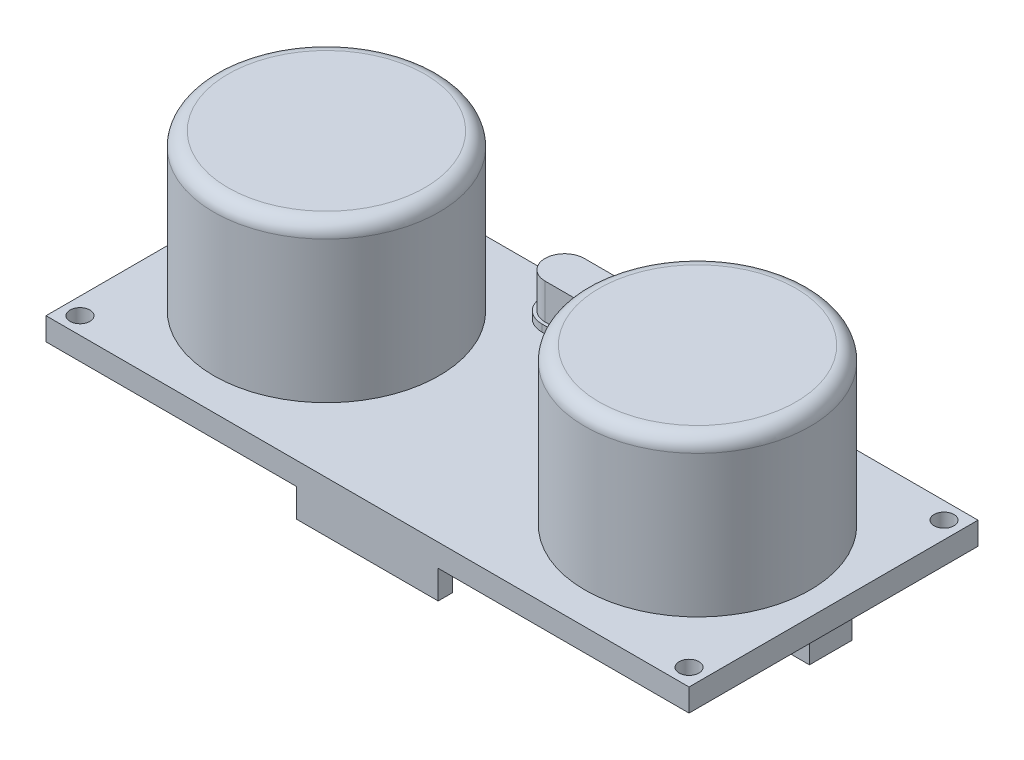
SolidWorks part; units mm, degrees
ref_plane "Alzado" through (0, 0, 0) normal (0, 0, 1) x (1, 0, 0)
ref_plane "Planta" through (0, 0, 0) normal (0, 1, 0) x (1, 0, 0)
ref_plane "Vista lateral" through (0, 0, 0) normal (1, 0, 0) x (0, 0, -1)
sketch "Croquis1" plane through (0, 0, 0) normal (0, 1, 0) x (1, 0, 0)
  line L1 (-22.7, 10.2) -> (22.7, 10.2)
  line L2 (-22.7, 10.2) -> (-22.7, -10.2)
  line L3 (-22.7, -10.2) -> (22.7, -10.2)
  line L4 (22.7, 10.2) -> (22.7, -10.2)
  line L5 (-22.7, 10.2) -> (22.7, -10.2) construction
  line L6 (-22.7, -10.2) -> (22.7, 10.2) construction
  point P0 (0, 0)
  dimension "D1" = 45.4
  dimension "D2" = 20.4
extrude "Saliente-Extruir1" add sketch "Croquis1" along normal blind 1.6
sketch "Croquis2" plane through (0, 1.6, 0) normal (0, 1, 0) x (1, 0, 0)
  line L5 (-21.5, 9) -> (21.5, -9) construction
  line L6 (-21.5, -9) -> (21.5, 9) construction
  circle A0 centre (-21.5, 9) radius 0.7
  circle A1 centre (21.5, 9) radius 0.7
  circle A2 centre (21.5, -9) radius 0.7
  circle A3 centre (-21.5, -9) radius 0.7
  point P0 (0, 0)
  dimension "D3" = 1.4
  dimension "D1" = 43
  dimension "D2" = 18
extrude "Cortar-Extruir1" cut sketch "Croquis2" against normal blind 1
sketch "Croquis3" plane through (0, 1.6, 0) normal (0, 1, 0) x (1, 0, 0)
  line L0 (0, 10.2) -> (0, -10.2) construction
  line L1 (22.7, 10.2) -> (-22.7, 10.2) construction
  line L2 (-22.7, -10.2) -> (22.7, -10.2) construction
  line L3 (-4.2022, 7.9196) -> (4.2022, 7.9196) construction
  line L4 (-4.2022, 9.5358) -> (4.2022, 9.5358)
  line L5 (-4.2022, 6.3033) -> (4.2022, 6.3033)
  line L6 (-4.2022, 7.9196) -> (4.2022, 7.9196) construction
  line L7 (-4.2022, 9.3049) -> (4.2022, 9.3049)
  line L8 (-4.2022, 6.5342) -> (4.2022, 6.5342)
  arc A0 (-4.2022, 9.5358) -> (-4.2022, 6.3033) centre (-4.2022, 7.9196) ccw
  arc A1 (4.2022, 6.3033) -> (4.2022, 9.5358) centre (4.2022, 7.9196) ccw
  arc A2 (-4.2022, 9.3049) -> (-4.2022, 6.5342) centre (-4.2022, 7.9196) ccw
  arc A3 (4.2022, 6.5342) -> (4.2022, 9.3049) centre (4.2022, 7.9196) ccw
  point P8 (0, 7.9196)
  point P15 (0, 7.9196)
extrude "Saliente-Extruir2" add sketch "Croquis3" along normal blind 0.5 contours L8 A3 L7 A2 | L5 A1 L4 A0
sketch "Croquis8" plane through (0, 1.6, 0) normal (0, 1, 0) x (1, 0, 0)
  line L0 (-4.2022, 9.3049) -> (4.2022, 9.3049) construction
  line L1 (-4.2022, 6.5342) -> (4.2022, 6.5342) construction
  line L2 (-4.2022, 9.3049) -> (4.2022, 9.3049)
  line L3 (-4.2022, 6.5342) -> (4.2022, 6.5342)
  arc A0 (4.2022, 6.5342) -> (4.2022, 9.3049) centre (4.2022, 7.9196) ccw construction
  arc A1 (-4.2022, 9.3049) -> (-4.2022, 6.5342) centre (-4.2022, 7.9196) ccw construction
  arc A2 (4.2022, 6.5342) -> (4.2022, 9.3049) centre (4.2022, 7.9196) ccw
  arc A3 (-4.2022, 9.3049) -> (-4.2022, 6.5342) centre (-4.2022, 7.9196) ccw
extrude "Saliente-Extruir3" add sketch "Croquis8" along normal blind 3
sketch "Croquis9" plane through (0, 1.6, 0) normal (0, 1, 0) x (1, 0, 0)
  line L0 (-21.05, 0) -> (21.05, 0) construction
  line L3 (-22.7, 10.2) -> (0, -10.2) construction
  line L4 (-22.7, -10.2) -> (22.7, -10.2) construction
  line L5 (0, -10.2) -> (22.7, 10.2) construction
  line L6 (-22.7, -10.2) -> (0, 10.2) construction
  line L7 (22.7, 10.2) -> (-22.7, 10.2) construction
  line L8 (0, 10.2) -> (22.7, -10.2) construction
  circle A0 centre (-13.1, 0) radius 7.95
  circle A1 centre (13.1, 0) radius 7.95
  point P2 (0, 0)
  dimension "D1" = 15.9
  dimension "D2" = 15.9
  dimension "D3" = 42.1
extrude "Saliente-Extruir4" add sketch "Croquis9" along normal blind 11
sketch "Croquis10" plane through (0, 0, 0) normal (0, -1, 0) x (1, 0, 0)
  line L0 (0, 10.2) -> (0, -10.2) construction
  line L1 (-22.7, 10.2) -> (22.7, 10.2) construction
  line L2 (22.7, -10.2) -> (-22.7, -10.2) construction
  line L3 (22.7, 0) -> (-22.7, 0) construction
  line L4 (22.7, 10.2) -> (22.7, -10.2) construction
  line L5 (-22.7, -10.2) -> (-22.7, 10.2) construction
  line L6 (-5.0127, 10.2) -> (4.9873, 10.2)
  line L7 (-5.0127, 10.2) -> (-5.0127, 9.2)
  line L8 (-5.0127, 9.2) -> (4.9873, 9.2)
  line L9 (4.9873, 9.2) -> (4.9873, 10.2)
  point P15 (-0.0127, 10.2)
  dimension "D1" = 10
  dimension "D2" = 1
extrude "Saliente-Extruir5" add sketch "Croquis10" along normal blind 2
fillet "Redondeo5" radius 1 2 edges at (13.1, 12.6, 7.95) (-13.1, 12.6, 7.95)
sketch "Croquis13" plane through (0, 0, 0) normal (0, -1, 0) x (1, 0, 0)
  line L1 (-4.5, 1.5) -> (4.5, 1.5)
  line L2 (-4.5, 1.5) -> (-4.5, -1.5)
  line L3 (-4.5, -1.5) -> (4.5, -1.5)
  line L4 (4.5, 1.5) -> (4.5, -1.5)
  line L5 (-4.5, 1.5) -> (4.5, -1.5) construction
  line L6 (-4.5, -1.5) -> (4.5, 1.5) construction
  point P0 (0, 0)
  dimension "D1" = 9
  dimension "D2" = 3
extrude "Saliente-Extruir6" add sketch "Croquis13" along normal blind 1.5
pattern_linear "MatrizL2" count 2 spacing 18 along (1, 0, 0) of "Saliente-Extruir6"
sketch "Croquis14" plane through (0, 0, 0) normal (0, -1, 0) x (1, 0, 0)
  line L0 (-22.7, -10.2) -> (-22.7, 10.2) construction
  line L1 (-20.7, 4.2078) -> (-17.7, 4.2078)
  line L2 (-20.7, 4.2078) -> (-20.7, -4.7922)
  line L3 (-20.7, -4.7922) -> (-17.7, -4.7922)
  line L4 (-17.7, 4.2078) -> (-17.7, -4.7922)
  line L5 (-20.7, 4.2078) -> (-17.7, -4.7922) construction
  line L6 (-20.7, -4.7922) -> (-17.7, 4.2078) construction
  point P0 (-19.2, -0.2922)
  dimension "D1" = 3
  dimension "D2" = 2
  dimension "D3" = 9
extrude "Saliente-Extruir7" add sketch "Croquis14" along normal blind 1.5
